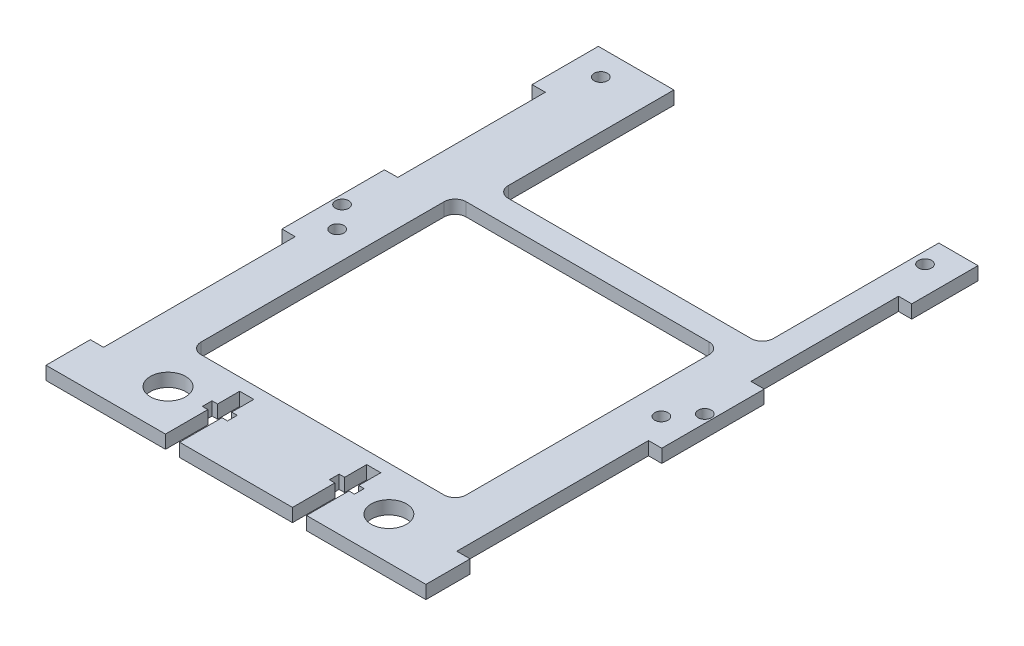
SolidWorks part; units mm, degrees
ref_plane "Front Plane" through (0, 0, 0) normal (0, 0, 1) x (1, 0, 0)
ref_plane "Top Plane" through (0, 0, 0) normal (0, 1, 0) x (1, 0, 0)
ref_plane "Right Plane" through (0, 0, 0) normal (1, 0, 0) x (0, 0, -1)
sketch "Sketch1" plane through (0, 0, 0) normal (0, 1, 0) x (1, 0, 0)
  line L0 (-43, 65.0267) -> (-25.8982, 65.0267)
  line L1 (-43, -60.0284) -> (-15.98, -60)
  line L2 (42.9735, 65.0086) -> (42.9735, 50.0086)
  line L3 (-25.8982, 65.0267) -> (-25.8982, 27.5267)
  line L4 (-43, 65.0267) -> (-43, 50.0267)
  line L5 (34.1019, 65.0086) -> (42.9735, 65.0086)
  line L6 (39.9747, -6.5914) -> (42.9747, -6.5914)
  line L7 (-23.3982, 25.0267) -> (31.6018, 25.0267)
  line L8 (34.1019, 65.0086) -> (34.1019, 27.5268)
  line L9 (0, 19.595) -> (0, -0.405) construction
  line L10 (0, -0.405) -> (36.703, -0.405) construction
  line L11 (-43, 16.6) -> (-40, 16.6267)
  line L12 (0, -0.405) -> (-36.703, -0.405) construction
  line L13 (42.9747, -6.5914) -> (42.9747, 16.6086)
  line L14 (15.9547, -59.9914) -> (42.9747, -59.9914)
  line L15 (15.9547, -59.9914) -> (15.9547, -50.3915)
  line L16 (15.9547, -50.3915) -> (17.2047, -50.3915)
  line L17 (17.2047, -50.3915) -> (17.2047, -48.2)
  line L18 (17.2047, -48.2) -> (15.98, -48.2)
  line L19 (15.98, -48.2) -> (15.98, -43.2)
  line L20 (15.98, -43.2) -> (12.78, -43.2)
  line L21 (12.78, -43.2) -> (12.78, -48.2)
  line L22 (12.78, -48.2) -> (11.53, -48.2)
  line L23 (11.53, -48.2) -> (11.53, -50.4)
  line L24 (11.53, -50.4) -> (12.78, -50.4)
  line L25 (12.78, -50.4) -> (12.78, -60)
  line L26 (-15.98, -60) -> (-15.98, -50.4)
  line L27 (-15.98, -50.4) -> (-17.23, -50.4)
  line L28 (-17.23, -50.4) -> (-17.23, -48.2)
  line L29 (-17.23, -48.2) -> (-15.98, -48.2)
  line L30 (-15.98, -48.2) -> (-15.98, -43.2)
  line L31 (-15.98, -43.2) -> (-12.78, -43.2)
  line L32 (-12.78, -43.2) -> (-12.78, -48.2)
  line L33 (-12.78, -48.2) -> (-11.53, -48.2)
  line L34 (-11.53, -48.2) -> (-11.53, -50.4)
  line L35 (-11.53, -50.4) -> (-12.78, -50.4)
  line L36 (-12.78, -50.4) -> (-12.78, -60)
  line L37 (-12.78, -60) -> (12.78, -60)
  line L38 (0, -5.405) -> (0, -40.405) construction
  line L39 (0, -40.405) -> (27.5, -40.405)
  line L40 (42.9747, 16.6086) -> (39.9747, 16.6086)
  line L41 (41.1322, 5) -> (-41, 5) construction
  line L42 (-36.703, -0.405) -> (-36.703, 59.285) construction
  line L43 (36.703, -0.405) -> (36.703, 59.285) construction
  line L44 (-25, -50.405) -> (25, -50.4) construction
  line L45 (0, -40.405) -> (-27.5, -40.405)
  line L46 (0, 19.595) -> (27.5, 19.595)
  line L47 (0, 19.595) -> (-27.5, 19.595)
  line L48 (-30, 17.095) -> (-30, -37.905)
  line L49 (42.9735, 50.0086) -> (39.9747, 50.0086)
  line L50 (39.9747, 50.0086) -> (39.9747, 16.6086)
  line L51 (30, -37.905) -> (30, 17.095)
  line L52 (42.9747, -59.9914) -> (42.9747, -49.9914)
  line L53 (42.9747, -49.9914) -> (39.9747, -49.9914)
  line L54 (39.9747, -49.9914) -> (39.9747, -6.5914)
  line L57 (-43, 50.0267) -> (-40, 50.0267)
  line L58 (-40, 50.0267) -> (-40, 16.6267)
  line L60 (-43, 16.6) -> (-43, -6.6)
  line L61 (-43, -6.6) -> (-40, -6.6)
  line L62 (-40, -6.6) -> (-40, -50)
  line L63 (-40, -50) -> (-43, -50)
  line L64 (-43, -50) -> (-43, -60.0284)
  line L66 (-30, -40.405) -> (-30, -50.405) construction
  line L67 (-30, -50.405) -> (-25, -50.405) construction
  line L68 (30, -40.405) -> (30, -50.4) construction
  line L69 (30, -50.4) -> (25, -50.4) construction
  circle A0 centre (-41, 5) radius 1.5
  circle A1 centre (-36.703, 59.285) radius 1.5
  circle A2 centre (36.703, 59.285) radius 1.5
  circle A3 centre (-36.703, -0.405) radius 1.5
  arc A4 (27.5, -40.405) -> (30, -37.905) centre (27.5, -37.905) ccw
  circle A5 centre (36.703, -0.405) radius 1.5
  circle A6 centre (-25, -50.405) radius 4
  circle A7 centre (25, -50.4) radius 4
  circle A8 centre (41.1322, 5) radius 1.5
  arc A9 (30, 17.095) -> (27.5, 19.595) centre (27.5, 17.095) ccw
  arc A10 (-27.5, 19.595) -> (-30, 17.095) centre (-27.5, 17.095) ccw
  arc A11 (-27.5, -40.405) -> (-30, -37.905) centre (-27.5, -37.905) cw
  arc A12 (-23.3982, 25.0267) -> (-25.8982, 27.5267) centre (-23.3982, 27.5267) cw
  arc A13 (31.6018, 25.0267) -> (34.1019, 27.5268) centre (31.6018, 27.5268) ccw
  point P0 (0, 0)
  dimension "D3" = 33.4
  dimension "D2" = 15
  dimension "D4" = 23.2
  dimension "D5" = 43.4
  dimension "D6" = 10
extrude "Boss-Extrude2" add sketch "Sketch1" along normal blind 3
